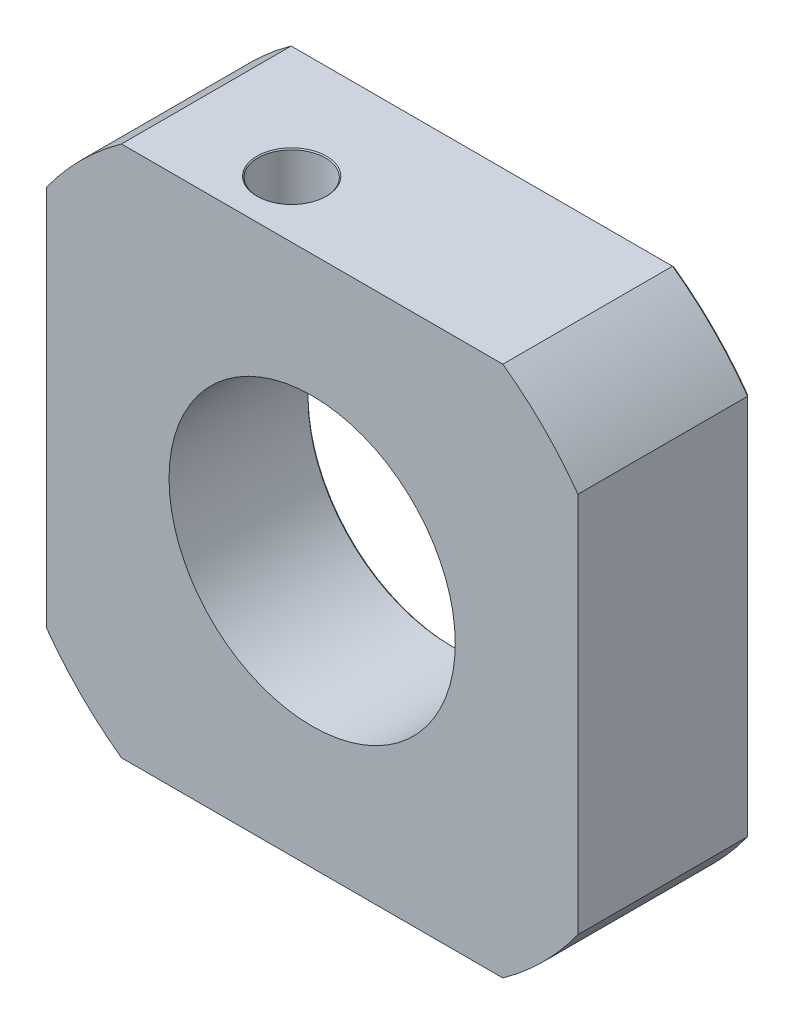
SolidWorks part; units mm, degrees
ref_plane "Front Plane" through (0, 0, 0) normal (0, 0, 1) x (1, 0, 0)
ref_plane "Top Plane" through (0, 0, 0) normal (0, 1, 0) x (1, 0, 0)
ref_plane "Right Plane" through (0, 0, 0) normal (1, 0, 0) x (0, 0, -1)
ref_plane "Plane1" through (0, 0, -111.25) normal (0, 0, -1) x (-1, 0, 0)
sketch "Sketch1" plane through (0, 0, -111.25) normal (0, 0, -1) x (-1, 0, 0)
  line L0 (-55.3953, -72.5599) -> (37.8784, -72.5599)
  line L1 (56.2415, -54.1968) -> (56.2415, 39.077)
  line L2 (37.8784, 57.4401) -> (-55.3953, 57.4401)
  line L3 (-73.7585, 39.077) -> (-73.7585, -54.1968)
  arc A0 (-73.7585, -54.1968) -> (-55.3953, -72.5599) centre (-8.7585, -7.5599) ccw
  arc A1 (37.8784, -72.5599) -> (56.2415, -54.1968) centre (-8.7585, -7.5599) ccw
  arc A2 (56.2415, 39.077) -> (37.8784, 57.4401) centre (-8.7585, -7.5599) ccw
  arc A3 (-55.3953, 57.4401) -> (-73.7585, 39.077) centre (-8.7585, -7.5599) ccw
extrude "Boss-Extrude1" add sketch "Sketch1" against normal blind 42
hole_wizard "CBORE for M64 Hex Head Bolt1" positions "Sketch3" profile "Sketch2" counterbore size "M64" standard "ANSI Metric"
sketch "Sketch3" plane through (0, 0, -111.25) normal (0, 0, -1) x (-1, 0, 0)
  point P0 (-8.7585, -7.5599)
sketch "Sketch2" plane through (8.7585, -7.5599, -111.25) normal (1, 0, 0) x (0, 1, 0)
  line L0 (0, 0) -> (0, 42)
  line L1 (0, 42) -> (35, 42)
  line L3 (35, 42) -> (35, 7.5)
  line L4 (35, 7.5) -> (55, 7.5)
  line L5 (55, 7.5) -> (55, 0)
  line L7 (55, 0) -> (0, 0)
  line L11 (0, -6.35) -> (0, 107.95) construction
  dimension "Thru Hole Dia." = 70
  dimension "Thru Hole Depth" = 42
  dimension "C'Bore Dia." = 110
  dimension "C'Bore Depth" = 7.5
hole_wizard "Ø16.5 (16.5) Diameter Hole1" positions "Sketch5" profile "Sketch4" hole size "Ø16.5" standard "ANSI Metric"
sketch "Sketch5" plane through (0, 57.4401, 0) normal (0, 1, 0) x (1, 0, 0)
  point P0 (-10.2415, 83.25)
sketch "Sketch4" plane through (-10.2415, 57.4401, -83.25) normal (1, 0, 0) x (0, 0, 1)
  line L0 (0, 0) -> (0, 35.6061)
  line L1 (0, 35.6061) -> (8.25, 35.6061)
  line L2 (8.25, 35.6061) -> (8.25, 0)
  line L5 (8.25, 0) -> (0, 0)
  line L11 (0, -6.35) -> (0, 107.95) construction
  dimension "Thru Hole Dia." = 16.5
  dimension "Thru Hole Depth" = 35.6061
hole_wizard "M6 Clearance Hole1" positions "Sketch7" profile "Sketch6" hole size "M6" standard "ANSI Metric"
sketch "Sketch7" plane through (0, 0, -111.25) normal (0, 0, -1) x (-1, 0, 0)
  point P0 (42.5068, -58.8252)
  point P1 (-60.0237, -58.8252)
  point P2 (-60.0237, 43.7053)
  point P3 (42.5068, 43.7053)
sketch "Sketch6" plane through (-42.5068, -58.8252, -111.25) normal (1, 0, 0) x (0, 1, 0)
  line L0 (0, 0) -> (0, 24.197)
  line L1 (0, 24.197) -> (3.3235, 22.2)
  line L2 (3.3235, 22.2) -> (3.3235, 0)
  line L5 (3.3235, 0) -> (0, 0)
  line L10 (0, 24.197) -> (-3.3235, 22.2) construction
  line L11 (0, -6.35) -> (0, 107.95) construction
  dimension "Hole Dia." = 6.647
  dimension "Hole Depth" = 22.2
  dimension "Drill Angle" = 118
chamfer "Chamfer1" distance 0.5 angle 45 10 edges at (-47.8101, 49.0086, -111.25) (-56.2415, -7.5599, -111.25) (8.7585, 57.4401, -111.25) (-47.8101, -64.1285, -111.25) (65.327, 49.0086, -111.25) (8.7585, -72.5599, -111.25) (73.7585, -7.5599, -111.25) (65.327, -64.1285, -111.25) (8.7585, 47.4401, -111.25) (8.7585, 27.4401, -103.75)
chamfer "Chamfer2" distance 1.1765 angle 45 4 edges at (-42.5068, 47.0288, -111.25) (60.0237, -55.5017, -111.25) (-42.5068, -55.5017, -111.25) (60.0237, 47.0288, -111.25)
chamfer "Chamfer3" distance 0.25 angle 45 1 edges at (-10.2415, 57.4401, -75)
